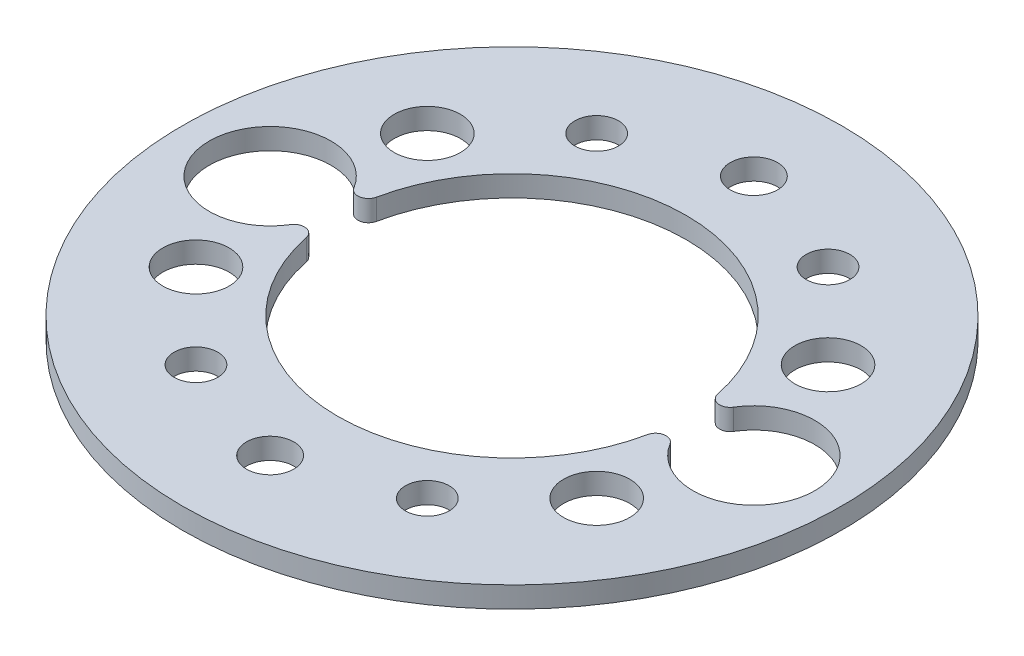
SolidWorks part; units mm, degrees
material "Aluminum 6061-T6 "
ref_plane "Front Plane" through (0, 0, 0) normal (0, 0, 1) x (1, 0, 0)
ref_plane "Top Plane" through (0, 0, 0) normal (0, 1, 0) x (1, 0, 0)
ref_plane "Right Plane" through (0, 0, 0) normal (1, 0, 0) x (0, 0, -1)
sketch "Sketch1" plane through (0, 0, 0) normal (0, 1, 0) x (1, 0, 0)
  line L0 (0, 0) -> (0, 36.5125) construction
  line L1 (0, 0) -> (-30.2459, 17.4625) construction
  line L2 (0, 0) -> (17.4625, 30.2459) construction
  line L3 (0, 0) -> (30.2459, -17.4625) construction
  line L4 (0, 0) -> (-17.4625, -30.2459) construction
  line L5 (44.9215, 0) -> (49.75, 0) construction
  line L6 (-17.4625, 30.2459) -> (0, 0) construction
  line L7 (0, 0) -> (17.4625, -30.2459) construction
  line L8 (-30.2459, -17.4625) -> (0, 0) construction
  line L9 (0, 0) -> (30.2459, 17.4625) construction
  line L10 (0, 0) -> (36.5125, 0) construction
  circle A0 centre (0, 0) radius 49.75
  arc A1 (-25.7486, -5.3031) -> (25.7486, -5.3031) centre (0, 0) ccw
  circle A2 centre (0, 36.5125) radius 3.5719
  circle A3 centre (0, -36.5125) radius 3.5719
  circle A4 centre (0, 0) radius 36.5125 construction
  arc A5 (-28.6583, 4.796) -> (-28.6583, -4.796) centre (-36.5125, 0) ccw
  arc A6 (28.6583, -4.796) -> (28.6583, 4.796) centre (36.5125, 0) ccw
  circle A7 centre (0, 36.5125) radius 6.5 construction
  arc A8 (25.7486, 5.3031) -> (-25.7486, 5.3031) centre (0, 0) ccw
  circle A9 centre (0, 0) radius 57.15 construction
  circle A10 centre (0, 0) radius 44.45 construction
  circle A11 centre (30.2459, -17.4625) radius 6.35 construction
  circle A12 centre (30.2459, -17.4625) radius 5
  circle A13 centre (17.4625, 30.2459) radius 3.3
  circle A14 centre (-30.2459, 17.4625) radius 5
  circle A15 centre (-17.4625, 30.2459) radius 3.3
  circle A16 centre (17.4625, 30.2459) radius 6 construction
  circle A17 centre (-17.4625, -30.2459) radius 3.3
  circle A18 centre (17.4625, -30.2459) radius 3.3
  circle A19 centre (30.2459, 17.4625) radius 5
  circle A20 centre (-30.2459, -17.4625) radius 5
  circle A21 centre (0, 0) radius 25.4 construction
  arc A22 (25.7486, 5.3031) -> (28.6583, 4.796) centre (27.3034, 5.6234) ccw
  arc A23 (25.7486, -5.3031) -> (28.6583, -4.796) centre (27.3034, -5.6234) cw
  arc A24 (-28.6583, 4.796) -> (-25.7486, 5.3031) centre (-27.3034, 5.6234) ccw
  arc A25 (-28.6583, -4.796) -> (-25.7486, -5.3031) centre (-27.3034, -5.6234) cw
  circle A26 centre (-36.5125, 0) radius 9.2027 construction
  dimension "D2" = 18.4055
  dimension "D3" = 73.025
  dimension "D4" = 13
  dimension "D6" = 114.3
  dimension "D7" = 99.5
  dimension "D8" = 88.9
  dimension "D9" = 12.7
  dimension "D10" = 30
  dimension "D5" = 6.6
  dimension "D14" = 12
  dimension "D15" = 10
  dimension "D17" = 50.8
  dimension "D18" = 26.289
  dimension "D19" = 1.5875
  dimension "D20" = 7.1437
  dimension "D11" = 30
  dimension "D12" = 30
  dimension "D13" = 30
  dimension "D16" = 69.85
extrude "Boss-Extrude1" add sketch "Sketch1" along normal blind 3.175
sketch "Sketch2" [suppressed] plane through (0, 3.175, 0) normal (0, 1, 0) x (1, 0, 0)
  circle A0 centre (0, 35.7188) radius 6.5
  circle A1 centre (0, -35.7188) radius 6.5
  dimension "D1" = 13
extrude "Upper GS FEA" [suppressed] cut sketch "Sketch2" against normal blind 0.0254
sketch "Sketch3" [suppressed] plane through (0, 0, 0) normal (0, -1, 0) x (1, 0, 0)
  circle A0 centre (17.4625, 30.2459) radius 6
  circle A1 centre (-17.4625, 30.2459) radius 6
  circle A2 centre (17.4625, -30.2459) radius 6
  circle A3 centre (-17.4625, -30.2459) radius 6
  dimension "D1" = 12
extrude "Upper Bolt FEA" [suppressed] cut sketch "Sketch3" against normal blind 0.0254
sketch "Sketch6" [suppressed] plane through (0, 3.175, 0) normal (0, 1, 0) x (1, 0, 0)
  circle A0 centre (-30.2459, 17.4625) radius 6.35
  circle A1 centre (-30.2459, -17.4625) radius 6.35
  circle A2 centre (30.2459, -17.4625) radius 6.35
  circle A3 centre (30.2459, 17.4625) radius 6.35
  dimension "D1" = 12.7
extrude "Lower Rivet FEA" [suppressed] cut sketch "Sketch6" against normal blind 0.0254
sketch "Sketch7" plane through (0, 0, 0) normal (0, -1, 0) x (1, 0, 0)
  line L0 (43.8132, 20.4356) -> (43.0738, 20.0907)
  line L1 (45.9093, 12.3014) -> (50.9526, 13.6527)
  line L2 (50.9526, -13.6527) -> (45.9093, -12.3014)
  line L3 (43.0738, -20.0907) -> (43.8132, -20.4356)
  circle A0 centre (45.2454, -16.4705) radius 1.75
  circle A1 centre (45.2454, 16.4705) radius 1.75
  arc A2 (43.0738, 20.0907) -> (45.9093, 12.3014) centre (44.8325, 16.3201) ccw
  arc A3 (50.9526, 13.6527) -> (50.9526, -13.6527) centre (0, 0) ccw
  arc A4 (45.9093, -12.3014) -> (43.0738, -20.0907) centre (44.8325, -16.3201) ccw
  arc A5 (43.8132, 20.4356) -> (43.8132, -20.4356) centre (2.1, 0) ccw
extrude "Lower Retainer Ring FEA" [suppressed] cut sketch "Sketch7" against normal blind 0.0254
sketch "Sketch8" plane through (0, 0, 0) normal (0, 1, 0) x (1, 0, 0)
  line L0 (0, -60.2275) -> (0, 60.2275)
  arc A0 (0, 60.2275) -> (0, -60.2275) centre (0, 0) ccw
extrude "Half FEA" [suppressed] cut sketch "Sketch8" along normal through all
